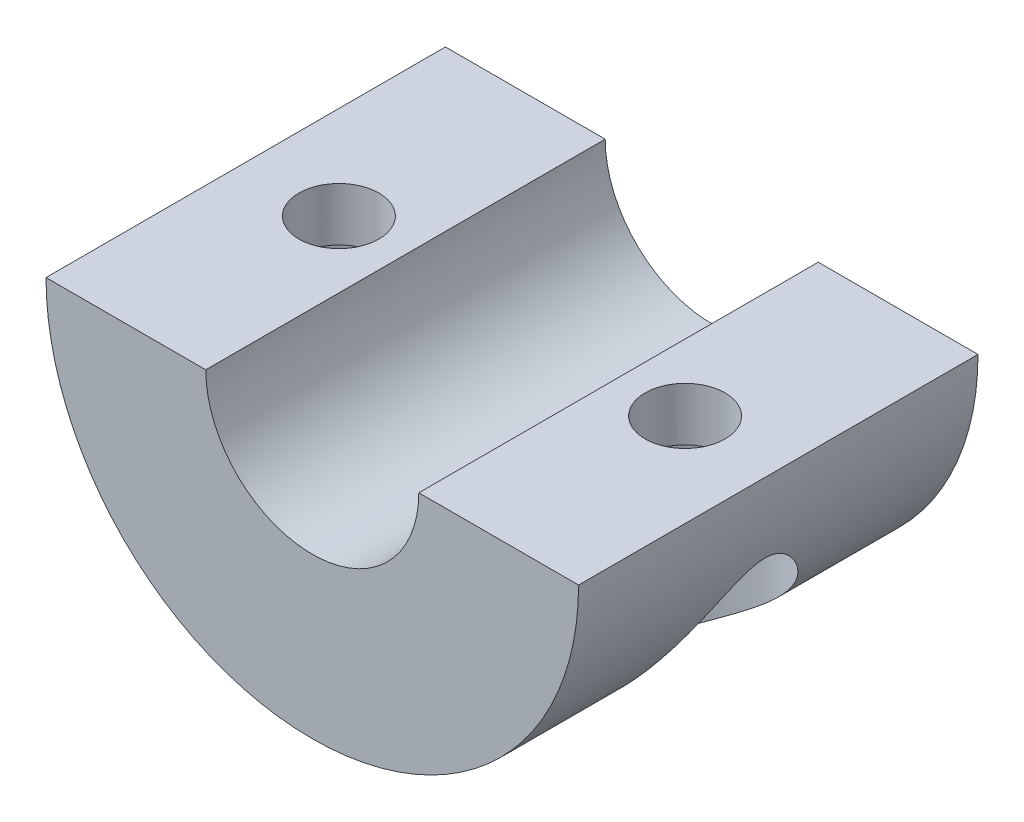
SolidWorks part; units mm, degrees
ref_plane "Спереди" through (0, 0, 0) normal (0, 0, 1) x (1, 0, 0)
ref_plane "Сверху" through (0, 0, 0) normal (0, 1, 0) x (1, 0, 0)
ref_plane "Справа" through (0, 0, 0) normal (1, 0, 0) x (0, 0, -1)
sketch "Sketch1" plane through (0, 0, 0) normal (0, 0, 1) x (1, 0, 0)
  line L0 (-10, 0) -> (10, 0)
  circle A0 centre (0, 0) radius 10
  circle A1 centre (0, 0) radius 4
  dimension "D1" = 8
  dimension "D2" = 6
extrude "Boss-Extrude1" add sketch "Sketch1" along normal blind 15 contours A1 L0 A0
ref_plane "Plane1" through (0, -2, 0) normal (0, 1, 0) x (1, 0, 0)
sketch "Sketch2" plane through (0, -2, 0) normal (0, 1, 0) x (1, 0, 0)
  line L0 (10, -15) -> (10, 0) construction
  line L1 (10, 0) -> (-10, 0) construction
  circle A0 centre (6.5, -7.5) radius 3
  dimension "D1" = 6
  dimension "D2" = 3.5
  dimension "D3" = 7.5
extrude "Cut-Extrude1" cut sketch "Sketch2" against normal blind 15
sketch "Sketch3" plane through (0, -2, 0) normal (0, -1, 0) x (1, 0, 0)
  circle A0 centre (6.5, 7.5) radius 1.5
  dimension "D1" = 3
extrude "Cut-Extrude2" cut sketch "Sketch3" against normal blind 15
mirror "Mirror1" about plane through (0, 0, 0) normal (1, 0, 0) of "Cut-Extrude2", "Cut-Extrude1"
